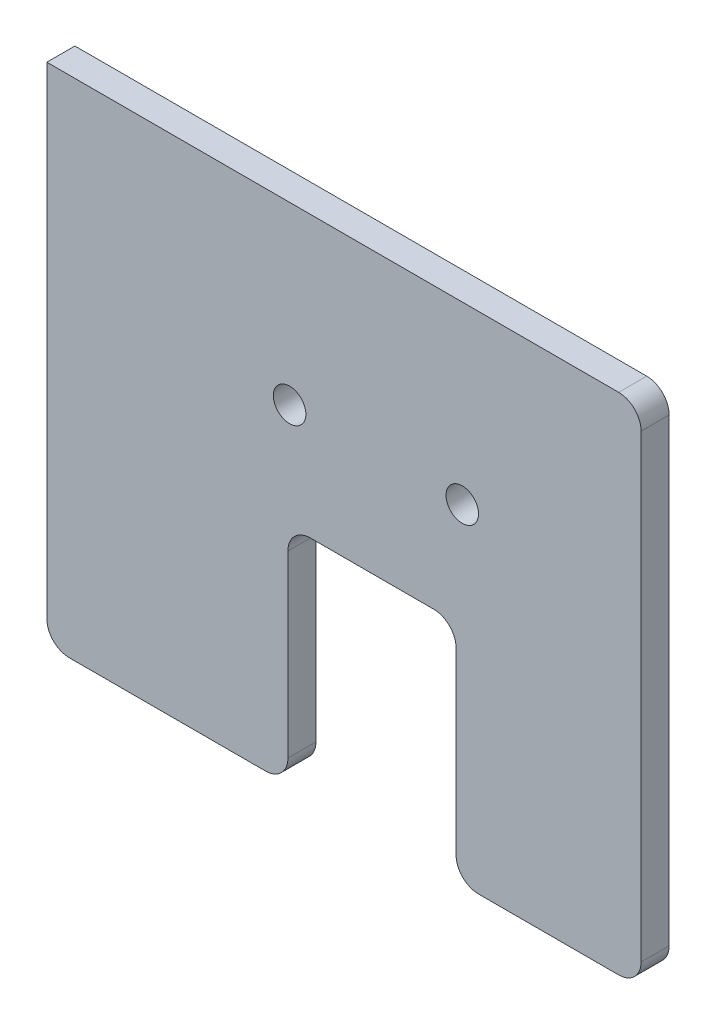
SolidWorks part; units mm, degrees
ref_plane "Alzado" through (0, 0, 0) normal (0, 0, 1) x (1, 0, 0)
ref_plane "Planta" through (0, 0, 0) normal (0, 1, 0) x (1, 0, 0)
ref_plane "Vista lateral" through (0, 0, 0) normal (1, 0, 0) x (0, 0, -1)
sketch "Croquis1" plane through (0, 0, 0) normal (0, 0, 1) x (1, 0, 0)
  line L0 (0, 0) -> (0, 45)
  line L1 (0, 45) -> (53, 45)
  line L2 (53, 45) -> (53, 0)
  line L3 (53, 0) -> (36.5, 0)
  line L4 (36.5, 0) -> (36.5, 20)
  line L5 (36.5, 20) -> (21.5, 20)
  line L6 (21.5, 20) -> (21.5, 0)
  line L7 (21.5, 0) -> (0, 0)
  dimension "D1" = 45
  dimension "D2" = 53
  dimension "D3" = 16.5
  dimension "D4" = 20
  dimension "D5" = 15
extrude "Saliente-Extruir1" add sketch "Croquis1" along normal blind 2.5
sketch "Croquis2" plane through (0, 0, 2.5) normal (0, 0, 1) x (1, 0, 0)
  line L1 (0, 45) -> (0, 0) construction
  line L4 (53, 0) -> (53, 45) construction
  line L5 (53, 45) -> (0, 45) construction
  circle A0 centre (37.05, 29.3545) radius 1.45
  circle A1 centre (21.65, 29.3545) radius 1.45
  point P4 (35.6, 29.3545)
  point P5 (23.1, 29.3545)
  point P6 (53, 22.5)
  point P9 (38.5, 29.3545)
  dimension "D2" = 2.9
  dimension "D4" = 2.9
  dimension "D1" = 35.6
  dimension "D3" = 12.5
  dimension "D5" = 15.6455
extrude "Cortar-Extruir1" cut sketch "Croquis2" against normal blind 2.5
fillet "Redondeo1" radius 2 7 edges at (0, 0, 1.25) (53, 45, 1.25) (53, 0, 1.25) (21.5, 0, 1.25) (36.5, 0, 1.25) (36.5, 20, 1.25) (21.5, 20, 1.25)
